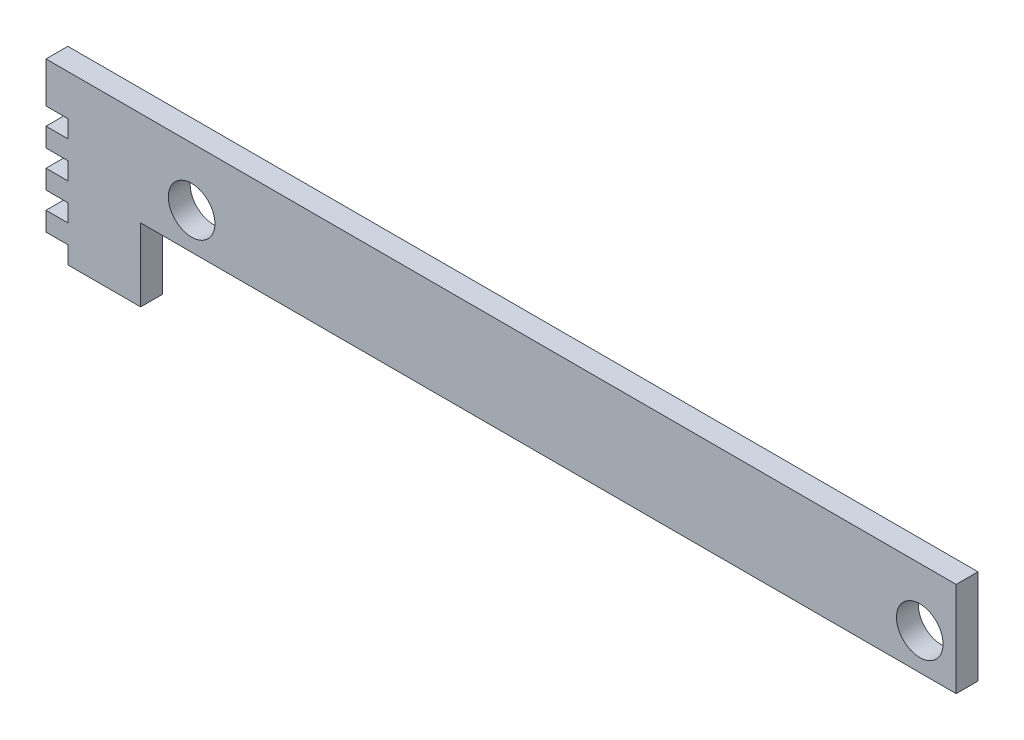
SolidWorks part; units mm, degrees
ref_plane "Plan de face" through (0, 0, 0) normal (0, 0, 1) x (1, 0, 0)
ref_plane "Plan de dessus" through (0, 0, 0) normal (0, 1, 0) x (1, 0, 0)
ref_plane "Plan de droite" through (0, 0, 0) normal (1, 0, 0) x (0, 0, -1)
sketch "Esquisse1" plane through (0, 0, 0) normal (0, 0, 1) x (1, 0, 0)
  line L0 (0, 0) -> (0, 26)
  line L5 (0, 0) -> (-59.8, 0) construction
  line L101 (-250, 20) -> (-250, 14.8)
  line L103 (-250, 14.8) -> (-244, 14.8)
  line L104 (-244, 14.8) -> (-244, 10)
  line L105 (-244, 10) -> (-250, 10)
  line L106 (-250, 10) -> (-250, 4.8)
  line L107 (-250, 4.8) -> (-244, 4.8)
  line L108 (-244, 4.8) -> (-244, 0)
  line L109 (-244, 0) -> (-250, 0)
  line L110 (-250, 0) -> (-250, -5.2)
  line L111 (-250, -5.2) -> (-244, -5.2)
  line L112 (-244, -5.2) -> (-244, -10)
  line L113 (-244, -10) -> (-250, -10)
  line L114 (-250, -10) -> (-250, -15.2)
  line L115 (-250, -15.2) -> (-244, -15.2)
  line L116 (-244, -15.2) -> (-244, -20)
  line L117 (-244, -20) -> (-224, -20)
  line L118 (-244, -20) -> (-250, -20) [skipped]
  line L119 (-224, -20) -> (-224, 0)
  line L120 (-224, 0) -> (-59.8, 0)
  line L128 (-59.8, 0) -> (0, 0)
  line L129 (-59.8, 0) -> (-277.7246, 0) construction
  line L131 (-250, 20) -> (-250, 26)
  line L132 (-250, 26) -> (0, 26)
  circle A0 centre (-210, 10) radius 6.4
  circle A1 centre (-10, 10) radius 6.4
  point P3 (0, 0)
  dimension "D11" = 12.8
  dimension "D12" = 12.8
  dimension "D13" = 200
  dimension "D14" = 10
  dimension "D15" = 10
  dimension "D1" = 26
  dimension "D5" = 6
  dimension "D7" = 20
  dimension "D8" = 4.8
  dimension "D9" = 5.2
  dimension "D10" = 4
extrude "Boss.-Extru.1" add sketch "Esquisse1" along normal blind 6
